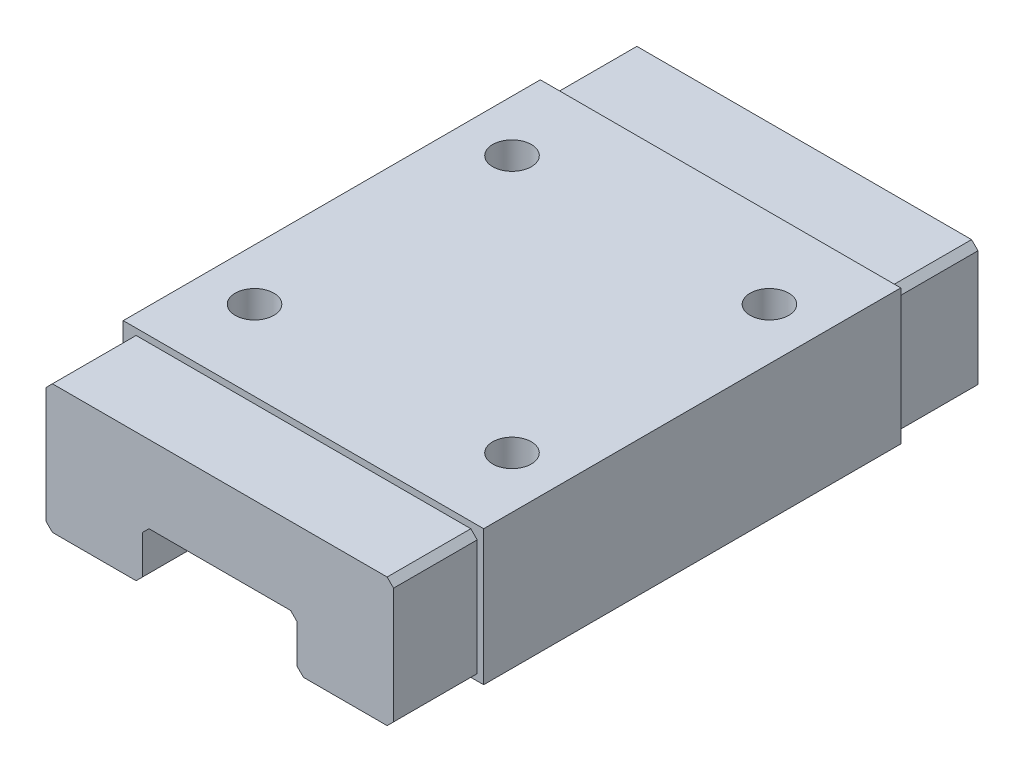
SolidWorks part; units mm, degrees
ref_plane "前视基准面" through (0, 0, 0) normal (0, 0, 1) x (1, 0, 0)
ref_plane "上视基准面" through (0, 0, 0) normal (0, 1, 0) x (1, 0, 0)
ref_plane "右视基准面" through (0, 0, 0) normal (1, 0, 0) x (0, 0, -1)
sketch "草图1" plane through (0, 0, 0) normal (0, 0, 1) x (1, 0, 0)
  line L0 (0, 17.8908) -> (0, -13.8277) construction
  line L1 (-13.5, 0) -> (13.5, 0)
  line L2 (13.5, 0) -> (13.5, -10)
  line L3 (13.5, -10) -> (6, -10)
  line L4 (6, -10) -> (6, -6)
  line L5 (6, -6) -> (-6, -6)
  line L6 (-6, -10) -> (-6, -6)
  line L7 (-13.5, -10) -> (-6, -10)
  line L8 (-13.5, 0) -> (-13.5, -10)
  point P10 (0, -6)
  point P13 (0, 0)
  dimension "D1" = 27
  dimension "D2" = 7.5
  dimension "D3" = 10
  dimension "D4" = 4
extrude "凸台-拉伸1" add sketch "草图1" along normal blind 45.4
sketch "草图2" plane through (0, 0, 45.4) normal (0, 0, 1) x (1, 0, 0)
  line L0 (14, -10) -> (14, 0.5)
  line L1 (14, 0.5) -> (-14, 0.5)
  line L2 (-14, 0.5) -> (-14, -10)
  line L3 (-13.5, -10) -> (-14, -10)
  line L4 (13.5, -10) -> (14, -10)
  line L8 (13.5, -10) -> (13.5, 0)
  line L9 (13.5, 0) -> (-13.5, 0)
  line L10 (-13.5, 0) -> (-13.5, -10)
  line L11 (-13.5, -10) -> (-6, -10)
  line L12 (-6, -10) -> (-6, -6)
  line L13 (-6, -6) -> (6, -6)
  line L14 (6, -6) -> (6, -10)
  line L15 (6, -10) -> (13.5, -10)
  line L16 (13.5, -10) -> (13.5, 0)
  line L17 (13.5, 0) -> (-13.5, 0)
  line L18 (-13.5, 0) -> (-13.5, -10)
  dimension "D1" = 0
  dimension "D2" = 0.5
extrude "凸台-拉伸2" add sketch "草图2" against normal blind 32.4 from offset 6.5 offset against normal yes
chamfer "倒角1" distance 0.5 angle 45 12 edges at (13.5, 0, 3.25) (13.5, 0, 42.15) (-13.5, 0, 3.25) (-13.5, 0, 42.15) (-13.5, -10, 3.25) (-13.5, -10, 42.15) (-6, -10, 22.7) (-6, -6, 22.7) (6, -6, 22.7) (6, -10, 22.7) (13.5, -10, 3.25) (13.5, -10, 42.15)
sketch "草图3" plane through (0, 0.5, 0) normal (0, 1, 0) x (1, 0, 0)
  line L0 (0, 0) -> (0, -45.4) construction
  line L1 (13, -45.4) -> (-13, -45.4) construction
  line L2 (-14, -22.7) -> (14, -22.7) construction
  line L3 (-14, -6.5) -> (-14, -38.9) construction
  line L4 (14, -6.5) -> (14, -38.9) construction
  circle A0 centre (10, -12.7) radius 1.5
  circle A1 centre (10, -32.7) radius 1.5
  circle A2 centre (-10, -32.7) radius 1.5
  circle A3 centre (-10, -12.7) radius 1.5
  dimension "D1" = 3
  dimension "D2" = 20
  dimension "D3" = 20
  dimension "D4" = 2.5
extrude "切除-拉伸1" cut sketch "草图3" against normal blind 3.5
